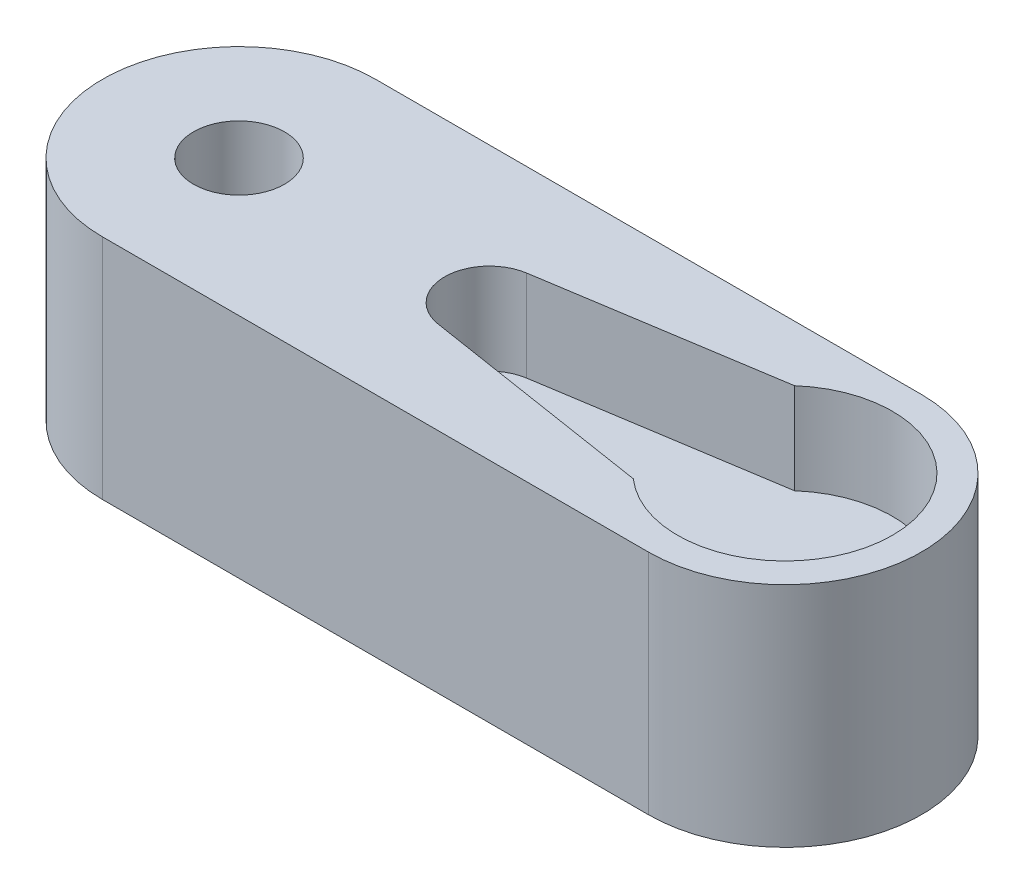
SolidWorks part; units mm, degrees
ref_plane "Front Plane" through (0, 0, 0) normal (0, 0, 1) x (1, 0, 0)
ref_plane "Top Plane" through (0, 0, 0) normal (0, 1, 0) x (1, 0, 0)
ref_plane "Right Plane" through (0, 0, 0) normal (1, 0, 0) x (0, 0, -1)
sketch "Sketch3" plane through (0, 0, 0) normal (0, 1, 0) x (1, 0, 0)
  line L0 (-25.4, 0) -> (5.08, 0) construction
  line L1 (-6.985, 0) -> (6.985, 0) construction
  line L2 (-25.4, 7.62) -> (5.08, 7.62)
  line L3 (-25.4, -7.62) -> (5.08, -7.62)
  arc A0 (-25.4, 7.62) -> (-25.4, -7.62) centre (-25.4, 0) ccw
  arc A1 (5.08, -7.62) -> (5.08, 7.62) centre (5.08, 0) ccw
  point P5 (-10.16, 0)
  dimension "D2" = 7.62
  dimension "D1" = 30.48
  dimension "D3" = 25.4
extrude "Boss-Extrude1" add sketch "Sketch3" along normal blind 12.7
sketch "Sketch4" plane through (0, 12.7, 0) normal (0, 1, 0) x (1, 0, 0)
  circle A0 centre (-25.4, 0) radius 2.54
  dimension "D1" = 5.08
extrude "Cut-Extrude3" cut sketch "Sketch4" against normal through all
sketch "Sketch5" plane through (0, 12.7, 0) normal (0, 1, 0) x (1, 0, 0)
  line L0 (-11.8081, -2.4697) -> (1.1114, -4.5)
  line L1 (1.1114, 4.5) -> (-11.8081, 2.4697)
  line L2 (-25.4, 0) -> (5.08, 0) construction
  line L3 (-25.4, -7.62) -> (5.08, -7.62) construction
  arc A0 (-11.8081, 2.4697) -> (-11.8081, -2.4697) centre (-11.42, 0) ccw
  arc A1 (1.1114, -4.5) -> (1.1114, 4.5) centre (5.08, 0) ccw
  dimension "D1" = 30.48
  dimension "D2" = 6
  dimension "D6" = 2.5
  dimension "D3" = 9
  dimension "D4" = 8.931
  dimension "D5" = 8.931
  dimension "D7" = 13.0781
  dimension "D8" = 13.0781
  dimension "D9" = 7.62
  dimension "D10" = 7.62
extrude "Cut-Extrude4" cut sketch "Sketch5" against normal blind 5.08
equation "\"TibiaLength\"= 4in"
equation "\"TibiaRadius\"= 0.3in"
equation "\"TibiaDistFromCentre\"= \"TibiaLength\" / 2"
equation "\"TibiaThickness\"= 0.5in"
equation "\"HoleRadius\"= 0.2in"
equation "\"D1@Sketch3\" = \"TibiaLength\" * 0.3"
equation "\"D2@Sketch3\"= \"TibiaRadius\""
equation "\"D3@Sketch3\"=\"TibiaDistFromCentre\"/2"
equation "\"D1@Boss-Extrude1\"= \"TibiaThickness\""
equation "\"D1@Sketch4\"= \"HoleRadius\""
equation "\"D1@Sketch5\"=\"TibiaLength\"*0.3"
